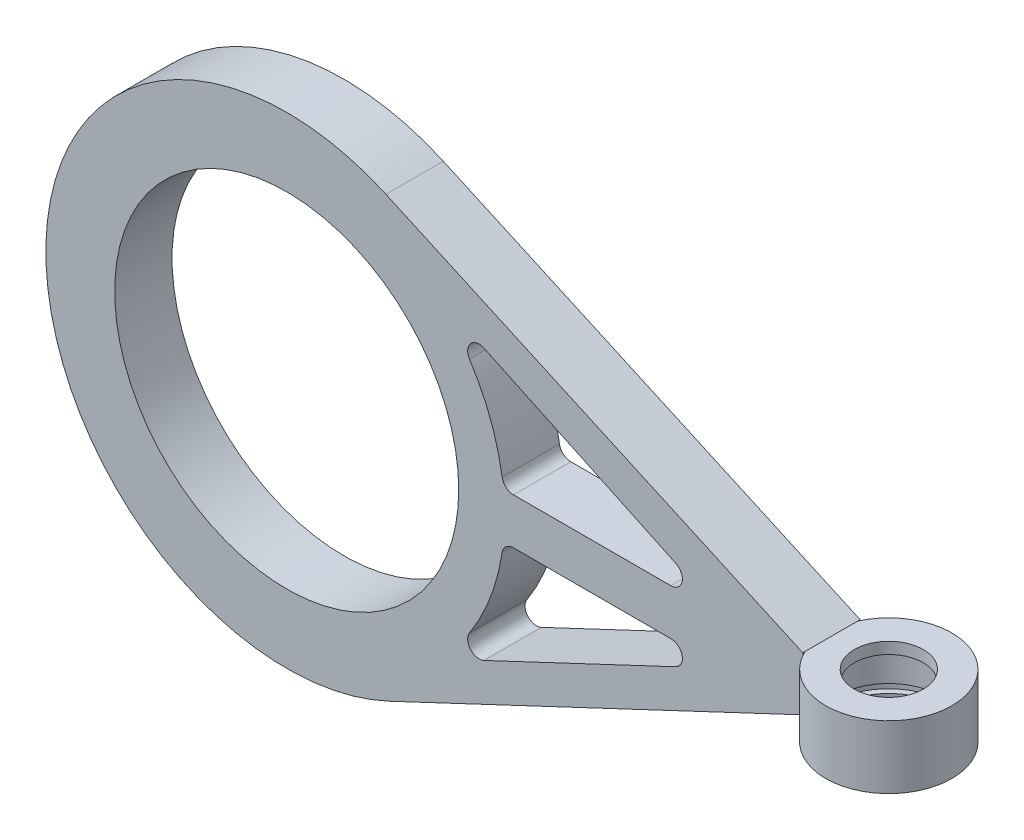
SolidWorks part; units mm, degrees
ref_plane "前视基准面" through (0, 0, 0) normal (0, 0, 1) x (1, 0, 0)
ref_plane "上视基准面" through (0, 0, 0) normal (0, 1, 0) x (1, 0, 0)
ref_plane "右视基准面" through (0, 0, 0) normal (1, 0, 0) x (0, 0, -1)
other "Configuration Table"
sketch "草图1" plane through (0, 0, 0) normal (0, 0, 1) x (1, 0, 0)
  circle A0 centre (0, 0) radius 42
  dimension "D1" = 84
extrude "凸台-拉伸1" add sketch "草图1" along normal blind 5
sketch "草图2" plane through (0, 0, 5) normal (0, 0, 1) x (1, 0, 0)
  line L0 (0, 0) -> (150.9371, 0) construction
  line L1 (100, 22.7173) -> (100, -21.6499) construction
  line L3 (89, 5.375) -> (100, 5.375)
  line L4 (89, 5.375) -> (89, -5.625)
  line L8 (89, -5.625) -> (100, -5.625)
  line L9 (100, 5.375) -> (100, -5.625)
  dimension "D2" = 11
  dimension "D1" = 100
  dimension "D3" = 5.375
  dimension "D4" = 11
revolve "旋转1" add sketch "草图2" angle 360 about L1
sketch "草图3" plane through (0, 0, 5) normal (0, 0, 1) x (1, 0, 0)
  line L0 (17.3147, 38.2649) -> (90, 5.375)
  line L1 (17.9116, -37.9891) -> (90, -4)
  line L4 (90, 5.375) -> (90, -4)
  circle A1 centre (0, 0) radius 42
  arc A2 (17.3147, 38.2649) -> (17.9116, -37.9891) centre (0, 0) ccw
  dimension "D2" = 90
  dimension "D3" = 5.375
  dimension "D4" = 4
  dimension "D1" = 0
extrude "凸台-拉伸2" add sketch "草图3" along normal mid plane 10
sketch "草图4" plane through (0, -5.625, 0) normal (0, -1, 0) x (1, 0, 0)
  circle A0 centre (100, 5) radius 6
  dimension "D1" = 12
extrude "切除-拉伸1" cut sketch "草图4" against normal blind 25
sketch "草图5" plane through (0, -5.625, 0) normal (0, -1, 0) x (1, 0, 0)
  circle A0 centre (100, 5) radius 9
  dimension "D1" = 18
extrude "切除-拉伸2" cut sketch "草图5" against normal offset from surface (9 mm away) 2 up to face at (100, 5.375, 11)
sketch "草图6" plane through (0, 3.375, 0) normal (0, -1, 0) x (1, 0, 0)
  circle A0 centre (100, 5) radius 10
  circle A1 centre (100, 5) radius 9 construction
  circle A2 centre (100, 5) radius 9 construction
  circle A3 centre (100, 5) radius 9
  circle M1 centre (100, 5) radius 9
  dimension "D1" = 1
extrude "切除-拉伸3" cut sketch "草图6" along normal blind 1.5 from offset 6.5 contours A0 M1 | A3
sketch "草图7" plane through (0, 0, 10) normal (0, 0, 1) x (1, 0, 0)
  line L0 (26.3566, -27.3739) -> (75.9309, -4)
  line L1 (0, 0) -> (55.8434, 0) construction
  line L2 (17.9116, -37.9891) -> (90, -4) construction
  line L4 (37.7889, -4) -> (75.9309, -4)
  line L5 (37.7889, 4) -> (75.9309, 4)
  line L6 (26.3566, 27.3739) -> (75.9309, 4)
  circle A0 centre (0, 0) radius 30
  arc A1 (26.3566, -27.3739) -> (37.7889, -4) centre (0, 0) ccw
  arc A2 (26.3566, 27.3739) -> (37.7889, 4) centre (0, 0) cw
  dimension "D1" = 60
  dimension "D3" = 8
  dimension "D2" = 6
  dimension "D4" = 4
extrude "切除-拉伸4" cut sketch "草图7" against normal blind 30
fillet "圆角1" radius 2 6 edges at (37.7889, 4, 5) (26.3566, 27.3739, 5) (75.9309, 4, 5) (75.9309, -4, 5) (37.7889, -4, 5) (26.3566, -27.3739, 5)
